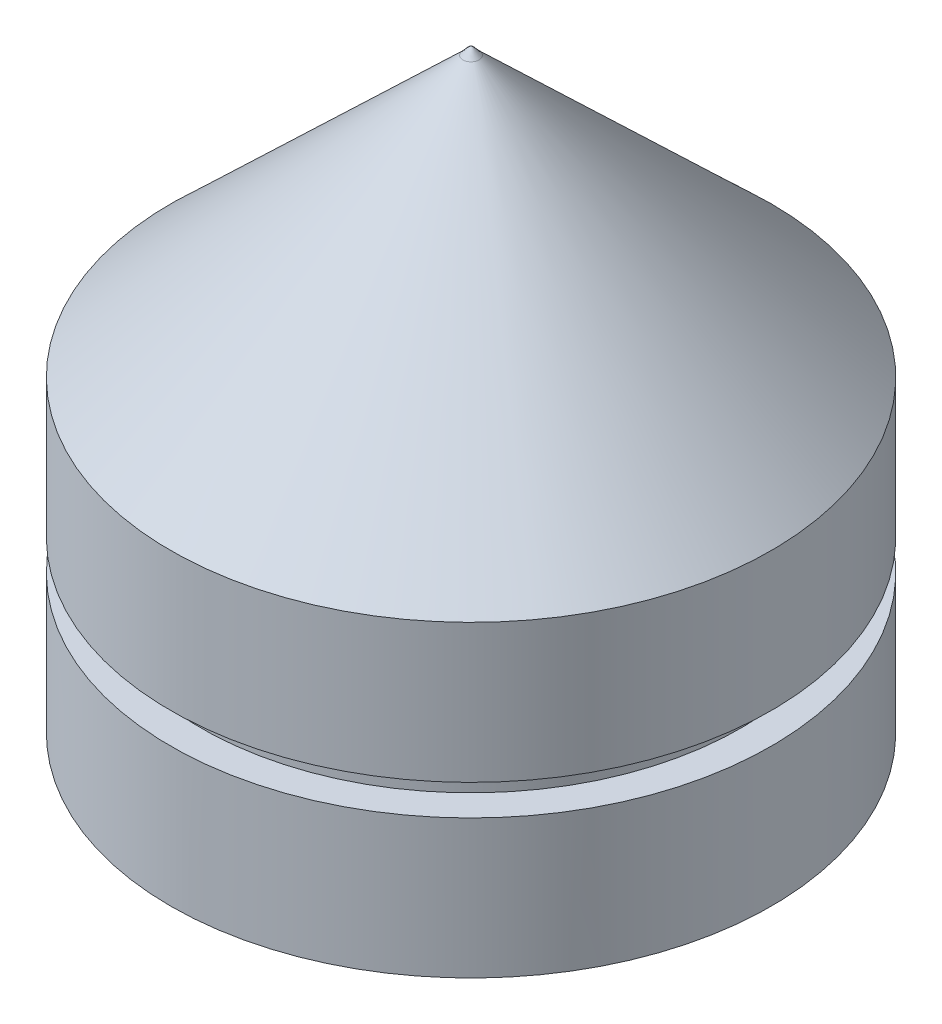
SolidWorks part; units mm, degrees
ref_plane "Front Plane" through (0, 0, 0) normal (0, 0, 1) x (1, 0, 0)
ref_plane "Top Plane" through (0, 0, 0) normal (0, 1, 0) x (1, 0, 0)
ref_plane "Right Plane" through (0, 0, 0) normal (1, 0, 0) x (0, 0, -1)
sketch "Sketch1" plane through (0, 0, 0) normal (0, 1, 0) x (1, 0, 0)
  circle A0 centre (0, 0) radius 9.75
  dimension "D1" = 19.5
extrude "Boss-Extrude1" add sketch "Sketch1" along normal blind 10
sketch "Sketch2" plane through (0, 0, 0) normal (0, 0, 1) x (1, 0, 0)
  line L0 (0, 10) -> (0, 19.3002)
  line L1 (9.75, 10) -> (-9.75, 10) construction
  line L2 (0, 19.3002) -> (9.75, 10)
  line L3 (9.75, 10) -> (0, 10)
  line L4 (0, 0) -> (0, 4.3089) construction
revolve "Revolve1" add sketch "Sketch2" angle 360 about L4
sketch "Sketch3" plane through (0, 0, 0) normal (0, 0, 1) x (1, 0, 0)
  line L0 (0, 19.3002) -> (0, 19.0502)
  line L1 (0, 19.0502) -> (0.2621, 19.0502)
  line L2 (9.75, 10) -> (0, 19.3002) construction
  line L3 (0.2621, 19.0502) -> (0, 19.3002)
  line L4 (0, 19.0502) -> (0, 19.1993) construction
  dimension "D1" = 0.25
revolve "Cut-Revolve1" cut sketch "Sketch3" angle 360 about L4
sketch "Sketch4" plane through (0, 0, 0) normal (0, 0, 1) x (1, 0, 0)
  line L0 (0, 19.0502) -> (0, 19.3002)
  line L1 (0.2621, 19.0502) -> (-0.2621, 19.0502) construction
  line L2 (0, 19.0502) -> (0, 18.7436) construction
  line L3 (0, 19.0502) -> (0.2621, 19.0502)
  spline S0 degree 3 poles (0, 19.3002) (0.0704, 19.2865) (0.134, 19.1895) (0.2621, 19.0502) knots 0.5 0.5 0.5 0.5 1 1 1 1
  dimension "D2" = 0.3665
  dimension "D1" = 0.25
revolve "Revolve2" add sketch "Sketch4" angle 360 about L2
sketch "Sketch5" plane through (0, 0, 0) normal (0, 0, 1) x (1, 0, 0)
  line L0 (-9.75, 5.5) -> (-9.75, 4.5)
  line L1 (-9.75, 10) -> (-9.75, 0) construction
  line L2 (9.75, 5) -> (-8.8311, 5) construction
  line L3 (9.75, 0) -> (9.75, 10) construction
  line L4 (-9.75, 5.5) -> (-8.75, 5.5)
  line L5 (-8.75, 5.5) -> (-8.75, 4.5)
  line L6 (-8.75, 4.5) -> (-9.75, 4.5)
  line L7 (0, 0) -> (0, 7.716) construction
  point P5 (-9.75, 5)
  dimension "D1" = 1
revolve "Cut-Revolve2" cut sketch "Sketch5" angle 360 about L7
